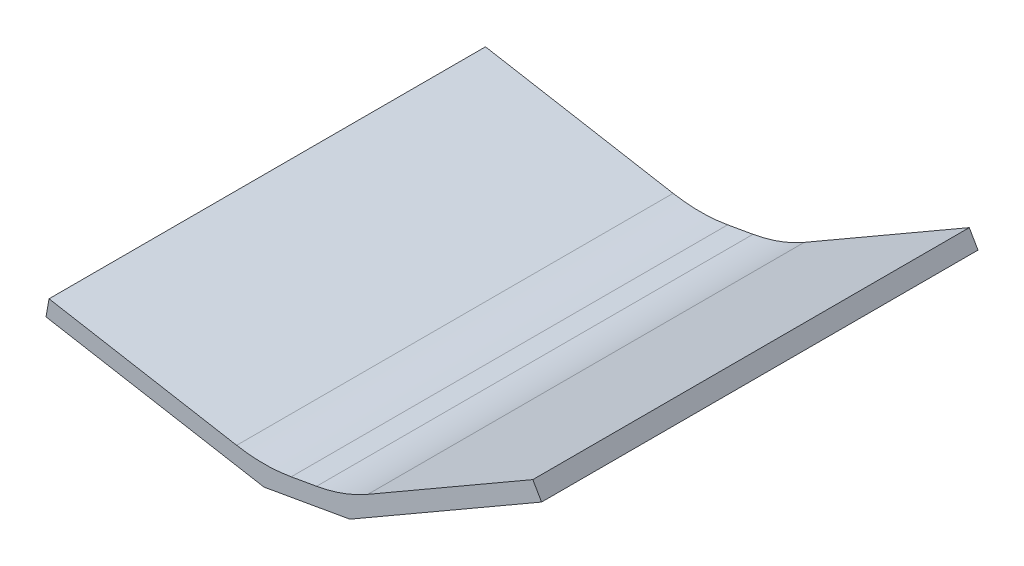
SolidWorks part; units mm, degrees
ref_plane "Front Plane" through (0, 0, 0) normal (0, 0, 1) x (1, 0, 0)
ref_plane "Top Plane" through (0, 0, 0) normal (0, 1, 0) x (1, 0, 0)
ref_plane "Right Plane" through (0, 0, 0) normal (1, 0, 0) x (0, 0, -1)
sketch "Sketch1" plane through (0, 0, 0) normal (0, 0, 1) x (1, 0, 0)
  line L0 (-45.9289, 4.2347) -> (-24.2783, 16.7347)
  line L1 (-55.0824, 2.6207) -> (-45.9289, 4.2347)
  line L3 (-55.0824, 0.5898) -> (-45.2343, 2.3263)
  line L5 (-24.2783, 16.7347) -> (-23.2783, 15.0026)
  line L6 (-23.2783, 15.0026) -> (-45.2343, 2.3263)
  line L8 (-55.0824, 2.6207) -> (-79.7026, 6.9619)
  line L9 (-79.7026, 6.9619) -> (-80.0499, 4.9923)
  line L10 (-80.0499, 4.9923) -> (-55.0824, 0.5898)
  dimension "D1" = 10
  dimension "D2" = 160
  dimension "D3" = 2
  dimension "D4" = 270
  dimension "D5" = 90
  dimension "D6" = 2
  dimension "D7" = 2
  dimension "D8" = 25
  dimension "D9" = 25
  dimension "D10" = 160
extrude "Boss-Extrude2" add sketch "Sketch1" along normal blind 50 contours L1 L0 L5 L6 L3 L10 L9 L8
fillet "Fillet7" radius 18 2 edges at (-55.0824, 2.6207, 25) (-45.9289, 4.2347, 25)
